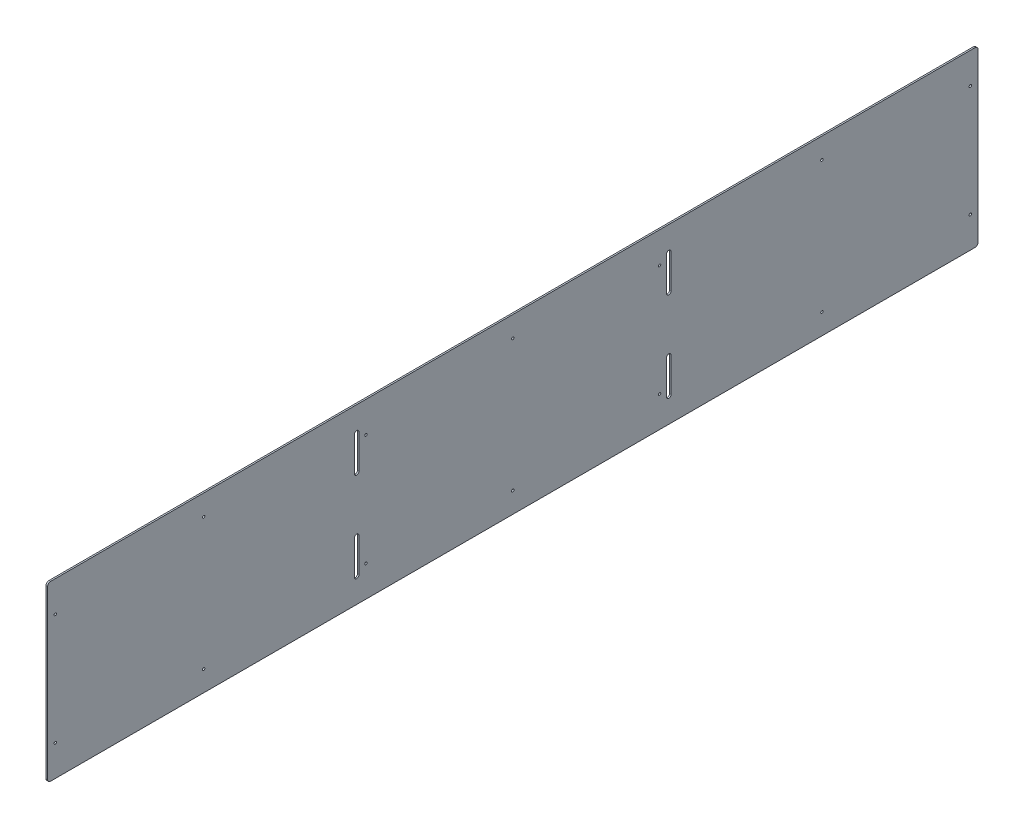
SolidWorks part; units mm, degrees
material "PC High Viscosity"
ref_plane "Front Plane" through (0, 0, 0) normal (0, 0, 1) x (1, 0, 0)
ref_plane "Top Plane" through (0, 0, 0) normal (0, 1, 0) x (1, 0, 0)
ref_plane "Right Plane" through (0, 0, 0) normal (1, 0, 0) x (0, 0, -1)
sketch "Sketch1" plane through (0, 0, 0) normal (1, 0, 0) x (0, 0, -1)
  line L1 (0, 0) -> (1911.35, 0)
  line L2 (0, 0) -> (0, 355.6)
  line L3 (0, 355.6) -> (1911.35, 355.6)
  line L4 (1911.35, 0) -> (1911.35, 355.6)
  dimension "D1" = 1911.35
  dimension "D2" = 355.6
extrude "Boss-Extrude1" add sketch "Sketch1" along normal blind 3.175
sketch "Sketch2" plane through (3.175, 0, 0) normal (1, 0, 0) x (0, 0, -1)
  line L0 (1911.35, 355.6) -> (0, 355.6) construction
  line L1 (0, 355.6) -> (0, 0) construction
  line L2 (0, 0) -> (1911.35, 0) construction
  line L3 (955.675, 313.182) -> (955.675, 42.418) construction
  circle A0 centre (15.875, 292.1) radius 2.4511
  circle A1 centre (654.05, 292.1) radius 2.4511
  circle A4 centre (320.675, 313.182) radius 2.4511
  circle A5 centre (955.675, 313.182) radius 2.4511
  circle A6 centre (1590.675, 313.182) radius 2.4511
  circle A7 centre (955.675, 42.418) radius 2.4511
  circle A8 centre (1590.675, 42.418) radius 2.4511
  circle A9 centre (320.675, 42.418) radius 2.4511
  circle A10 centre (15.875, 63.5) radius 2.4511
  circle A11 centre (654.05, 63.5) radius 2.4511
  circle A14 centre (1292.225, 292.1) radius 2.4511 [skipped]
  circle A15 centre (1930.4, 292.1) radius 2.4511 [skipped]
  circle A16 centre (1895.475, 63.5) radius 2.4511
  circle A17 centre (1895.475, 292.1) radius 2.4511
  circle A18 centre (1257.3, 63.5) radius 2.4511
  circle A19 centre (1257.3, 292.1) radius 2.4511
  dimension "D2" = 4.9022
  dimension "D4" = 4
  dimension "D6" = 4.9022
  dimension "D1" = 63.5
  dimension "D3" = 15.875
  dimension "D5" = 320.675
  dimension "D7" = 42.418
  dimension "D10" = 42.418
  dimension "D11" = 635
  dimension "D13" = 638.175
  dimension "D14" = 228.6
  dimension "D15" = 270.764
  dimension "D8" = 3
  dimension "D9" = 2
  dimension "D12" = 2
extrude "Cut-Extrude1" cut sketch "Sketch2" against normal through all
fillet "Fillet1" radius 6.35 4 edges at (1.5875, 0, -1911.35) (1.5875, 355.6, -1911.35) (1.5875, 0, 0) (1.5875, 355.6, 0)
sketch "Sketch3" plane through (3.175, 0, 0) normal (1, 0, 0) x (0, 0, -1)
  line L0 (654.05, 292.1) -> (654.05, 63.5) construction
  line L1 (1257.3, 292.1) -> (1257.3, 63.5) construction
  line L2 (635, 304.8) -> (635, 234.95) construction
  line L3 (639.7625, 304.8) -> (639.7625, 234.95)
  line L4 (630.2375, 304.8) -> (630.2375, 234.95)
  line L5 (1276.35, 304.8) -> (1276.35, 234.95) construction
  line L6 (1281.1125, 304.8) -> (1281.1125, 234.95)
  line L7 (1271.5875, 304.8) -> (1271.5875, 234.95)
  line L8 (0, 177.8) -> (1911.35, 177.8) construction
  line L9 (0, 349.25) -> (0, 6.35) construction
  line L10 (1911.35, 6.35) -> (1911.35, 349.25) construction
  line L11 (1276.35, 50.8) -> (1276.35, 120.65) construction
  line L12 (1281.1125, 50.8) -> (1281.1125, 120.65)
  line L13 (1271.5875, 50.8) -> (1271.5875, 120.65)
  line L14 (635, 50.8) -> (635, 120.65) construction
  line L15 (639.7625, 50.8) -> (639.7625, 120.65)
  line L16 (630.2375, 50.8) -> (630.2375, 120.65)
  arc A0 (639.7625, 304.8) -> (630.2375, 304.8) centre (635, 304.8) ccw
  arc A1 (630.2375, 234.95) -> (639.7625, 234.95) centre (635, 234.95) ccw
  arc A2 (1281.1125, 304.8) -> (1271.5875, 304.8) centre (1276.35, 304.8) ccw
  arc A3 (1271.5875, 234.95) -> (1281.1125, 234.95) centre (1276.35, 234.95) ccw
  arc A4 (1281.1125, 50.8) -> (1271.5875, 50.8) centre (1276.35, 50.8) cw
  arc A5 (1271.5875, 120.65) -> (1281.1125, 120.65) centre (1276.35, 120.65) cw
  arc A6 (639.7625, 50.8) -> (630.2375, 50.8) centre (635, 50.8) cw
  arc A7 (630.2375, 120.65) -> (639.7625, 120.65) centre (635, 120.65) cw
  point P10 (635, 269.875)
  point P17 (1276.35, 269.875)
  point P30 (1276.35, 85.725)
  point P37 (635, 85.725)
  dimension "D1" = 12.7
  dimension "D2" = 69.85
  dimension "D3" = 19.05
  dimension "D4" = 9.525
  dimension "D5" = 9.525
  dimension "D6" = 19.05
extrude "Cut-Extrude2" cut sketch "Sketch3" against normal through all
